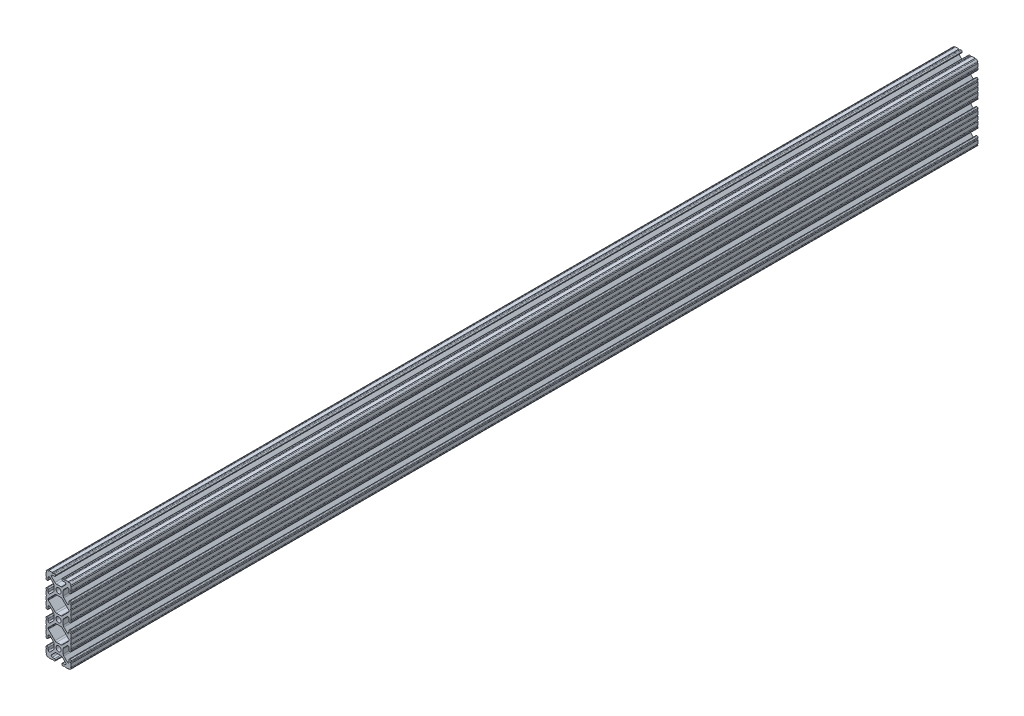
SolidWorks part; units mm, degrees
ref_plane "Front Plane" through (0, 0, 0) normal (0, 0, 1) x (1, 0, 0)
ref_plane "Top Plane" through (0, 0, 0) normal (0, 1, 0) x (1, 0, 0)
ref_plane "Right Plane" through (0, 0, 0) normal (1, 0, 0) x (0, 0, -1)
sketch "Sketch2" plane through (0, 0, 0) normal (0, 0, 1) x (1, 0, 0)
  line L0 (0, 38.1) -> (0, -38.1) construction
  line L1 (-12.7, 0) -> (12.7, 0) construction
  line L2 (3.2512, -38.1) -> (12.7, -38.1)
  line L3 (12.7, -38.1) -> (12.7, -28.6512)
  line L4 (3.2512, -38.1) -> (3.2512, -35.8902)
  line L5 (3.2512, -35.8902) -> (8.9276, -35.8902)
  line L6 (8.9276, -35.8902) -> (3.0856, -30.0482)
  line L7 (0, -25.4) -> (12.7, -38.1) construction
  line L8 (12.7, -28.6512) -> (10.4902, -28.6512)
  line L9 (10.4902, -28.6512) -> (10.4902, -34.3276)
  line L10 (10.4902, -34.3276) -> (4.6482, -28.4856)
  circle A0 centre (0, -25.4) radius 2.6035
  arc A1 (6.3485, -35.8902) -> (7.1039, -34.0665) centre (6.3485, -34.8219) ccw construction
  point P8 (0, -30.0482)
  dimension "Center Hole Diameter" = 5.207
  dimension "Rail Height" = 76.2
  dimension "Rail Width" = 25.4
  dimension "T-Slot Width" = 6.5024
  dimension "Slot Inner Width" = 14.8336
  dimension "Thickness" = 2.2098
  dimension "Slot Depth" = 5.842
  dimension "D1" = 2.2098
  dimension "D2" = 50.8
sketch "Sketch3" plane through (0, 0, 0) normal (1, 0, 0) x (0, 0, -1)
  line L0 (-457.2, -38.1) -> (457.2, -38.1) construction
  line L1 (-431.8, 0) -> (431.8, 0) construction
  dimension "Length" = 914.4
  dimension "D1" = 25.4
sketch "Sketch4" plane through (0, 0, 0) normal (0, 0, 1) x (1, 0, 0)
  line L0 (4.1904, -38.1) -> (10.1173, -38.1)
  line L1 (3.2512, -38.1) -> (12.7, -38.1) construction
  line L2 (3.2512, -38.1) -> (3.2512, -35.8902) construction
  line L3 (3.2512, -35.8902) -> (8.9276, -35.8902) construction
  line L4 (3.2512, -36.8294) -> (3.2512, -37.1608)
  line L5 (4.1904, -35.8902) -> (6.3485, -35.8902)
  line L6 (0, -30.0482) -> (2.164, -30.0482)
  line L7 (8.9276, -35.8902) -> (3.0856, -30.0482) construction
  line L8 (3.7373, -30.6999) -> (7.1039, -34.0665)
  line L9 (12.7, -38.1) -> (12.7, -28.6512) construction
  line L10 (10.4902, -34.3276) -> (4.6482, -28.4856) construction
  line L11 (10.4902, -28.6512) -> (10.4902, -34.3276) construction
  line L12 (10.4902, -31.7485) -> (10.4902, -29.5904)
  line L13 (12.7, -28.6512) -> (10.4902, -28.6512) construction
  line L14 (11.4294, -28.6512) -> (11.7608, -28.6512)
  line L15 (12.7, -29.5904) -> (12.7, -35.5173)
  line L16 (8.6665, -32.5039) -> (5.2999, -29.1373)
  line L17 (4.6482, -25.4) -> (4.6482, -27.564)
  line L19 (0, -30.0482) -> (0, -28.0035)
  line L20 (0, 38.1) -> (0, -38.1) construction
  line L21 (4.6482, -25.4) -> (2.6035, -25.4)
  arc A0 (3.2512, -37.1608) -> (4.1904, -38.1) centre (4.1904, -37.1608) ccw
  circle A1 centre (0, -25.4) radius 2.6035 construction
  arc A2 (3.2512, -36.8294) -> (4.1904, -35.8902) centre (4.1904, -36.8294) cw
  arc A3 (6.3485, -35.8902) -> (7.1039, -34.0665) centre (6.3485, -34.8219) ccw
  arc A4 (2.164, -30.0482) -> (3.7373, -30.6999) centre (2.164, -32.2732) cw
  arc A5 (10.1173, -38.1) -> (12.7, -35.5173) centre (10.1173, -35.5173) ccw
  arc A6 (8.6665, -32.5039) -> (10.4902, -31.7485) centre (9.4219, -31.7485) ccw
  arc A7 (10.4902, -29.5904) -> (11.4294, -28.6512) centre (11.4294, -29.5904) cw
  arc A8 (11.7608, -28.6512) -> (12.7, -29.5904) centre (11.7608, -29.5904) cw
  arc A9 (5.2999, -29.1373) -> (4.6482, -27.564) centre (6.8732, -27.564) cw
  arc A11 (0, -28.0035) -> (2.6035, -25.4) centre (0, -25.4) ccw
  dimension "D1" = 2.5827
  dimension "D2" = 2.225
  dimension "D3" = 0.9392
extrude "Boss-Extrude1" add sketch "Sketch4" along normal mid plane 914.4
sketch "Sketch5" plane through (0, 0, 0) normal (0, 0, 1) x (1, 0, 0)
  line L0 (3.2512, -38.1) -> (12.7, -38.1) construction
  line L1 (4.1904, -35.8902) -> (6.3485, -35.8902) construction
  line L3 (0, -25.4) -> (12.7, -38.1) construction
  line L4 (6.3485, -35.8902) -> (6.3485, -38.1) construction
  line L5 (8.9276, -35.8902) -> (3.0856, -30.0482) construction
  circle A0 centre (10.3562, -38.1) radius 0.5524
  circle A1 centre (5.796, -38.1) radius 0.5524
  circle A2 centre (12.7, -35.7562) radius 0.5525
  circle A3 centre (12.7, -31.196) radius 0.5525
  point P10 (5.2694, -35.8902)
  point P12 (9.4219, -31.7485)
  dimension "D1" = 1.1049
extrude "Cut-Extrude1" cut sketch "Sketch5" against normal through all both and the other way through all
mirror "Mirror1" about plane through (4.6482, -25.4, 457.2) normal (0, -1, 0) of bodies 137 134
sketch "Sketch6" plane through (0, 0, 0) normal (0, 0, 1) x (1, 0, 0)
  line L0 (12.7, -14.4914) -> (12.7, -12.7)
  line L1 (12.7, -12.7) -> (9.8037, -12.7)
  line L3 (9.8037, -12.7) -> (9.8037, -15.5963)
  line L4 (9.8037, -15.5963) -> (12.7, -15.5963)
  line L5 (6.3485, -12.7) -> (9.8037, -12.7) construction
  circle A0 centre (12.7, -15.0438) radius 0.5525 construction
  arc A1 (12.7, -14.4914) -> (12.7, -15.5963) centre (12.7, -15.0438) ccw
  arc A4 (9.8037, -12.7) -> (10.8954, -12.82) centre (10.3562, -12.7) ccw construction
extrude "Boss-Extrude2" add sketch "Sketch6" along normal mid plane 914.4
sketch "Sketch7" plane through (0, 0, 0) normal (0, 0, 1) x (1, 0, 0)
  line L0 (5.4206, -18.4168) -> (10.3284, -13.509)
  line L1 (3.7373, -20.1001) -> (7.1039, -16.7335) construction
  line L2 (10.4902, -13.1184) -> (10.4902, -12.7)
  line L3 (0, -12.7) -> (10.4902, -12.7)
  line L5 (0, -12.7) -> (5.4206, -18.4168)
  line L7 (0, 38.1) -> (0, -38.1) construction
  line L8 (6.3485, -12.7) -> (12.7, -12.7) construction
  arc A0 (10.3284, -13.509) -> (10.4902, -13.1184) centre (9.9377, -13.1184) ccw
  arc A3 (12.7, -14.4914) -> (12.7, -15.5963) centre (12.7, -15.0438) ccw construction
extrude "Cut-Extrude2" cut sketch "Sketch7" against normal through all both and the other way through all
mirror "Mirror2" about plane through (4.1904, -12.7, 457.2) normal (0, -1, 0) of bodies 139 135
other "SurfaceCut1"
mirror "Mirror3" about plane through (0, 0, 0) normal (1, 0, 0) of bodies 142 136
mirror "Mirror4" about plane through (0, 0, 0) normal (0, 1, 0) of bodies 140
equation "\"D1@Boss-Extrude1\"=\"Length@Sketch3\""
equation "\"D1@Sketch2\"=\"Thickness@Sketch2\""
equation "\"D2@Sketch4\"=\"Slot Inner Width@Sketch2\"*0.15"
equation "\"D1@Sketch4\"=\"D3@Sketch4\"*2.75"
equation "\"D3@Sketch4\"=\"Thickness@Sketch2\"*0.425"
equation "\"D1@Sketch5\"=\"Thickness@Sketch2\"*0.5"
equation "\"D1@Boss-Extrude2\"=\"Length@Sketch3\""
